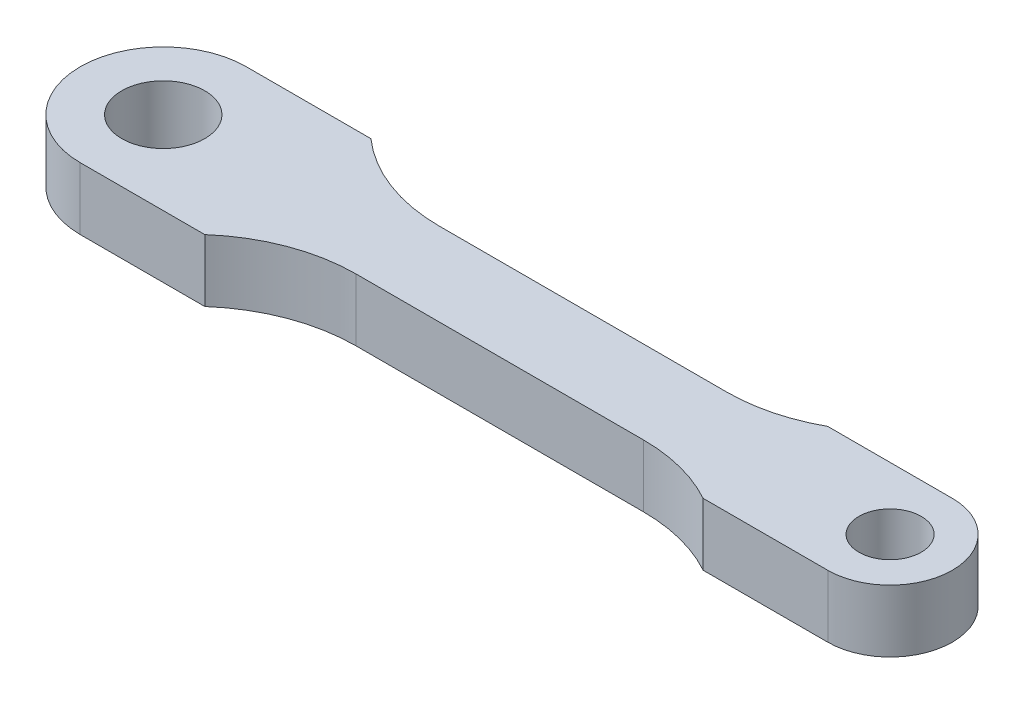
SolidWorks part; units mm, degrees
ref_plane "Front Plane" through (0, 0, 0) normal (0, 0, 1) x (1, 0, 0)
ref_plane "Top Plane" through (0, 0, 0) normal (0, 1, 0) x (1, 0, 0)
ref_plane "Right Plane" through (0, 0, 0) normal (1, 0, 0) x (0, 0, -1)
sketch "Sketch1" plane through (0, 0, 0) normal (0, 1, 0) x (1, 0, 0)
  line L1 (-17.5, 4) -> (-11.5, 4)
  line L3 (-17.5, -4) -> (-11.5, -4)
  line L5 (-11.5, 4) -> (11.5, 3)
  line L8 (-11.5, -4) -> (11.5, -3)
  line L9 (17.5, 3) -> (11.5, 3)
  line L10 (17.5, -3) -> (11.5, -3)
  arc A0 (-17.5, 4) -> (-17.5, -4) centre (-17.5, 0) ccw
  arc A1 (17.5, -3) -> (17.5, 3) centre (17.5, 0) ccw
  circle A2 centre (-17.5, 0) radius 2
  circle A3 centre (17.5, 0) radius 1.5
  point P0 (0, 0)
  point P2 (-21.5, 4)
  point P4 (20.5, 4)
  dimension "D1" = 4
  dimension "D4" = 3
  dimension "D2" = 4
  dimension "D5" = 35
  dimension "D6" = 17.5
extrude "Boss-Extrude1" add sketch "Sketch1" along normal mid plane 3
sketch "Sketch2" plane through (0, 1.5, 0) normal (0, 1, 0) x (1, 0, 0)
  line L1 (-11.5, 4) -> (11.5, 3)
  line L2 (-11.5, 0) -> (11.5, 0) construction
  line L4 (-6.2085, 2) -> (7.627, 2)
  line L6 (-11.5, 2) -> (11.5, 2) construction
  arc A2 (-11.5, 4) -> (-6.2085, 2) centre (-6.2085, 10) ccw
  arc A3 (7.627, 2) -> (11.5, 3) centre (7.627, 10) ccw
  dimension "D3" = 16
  dimension "D4" = 16
  dimension "D1" = 9.873
  dimension "D2" = 2
extrude "Cut-Extrude1" cut sketch "Sketch2" against normal blind 3 contours L4 A3 L1 A2
mirror "Mirror1" about plane through (0, 0, 0) normal (0, 0, 1) of "Cut-Extrude1"
